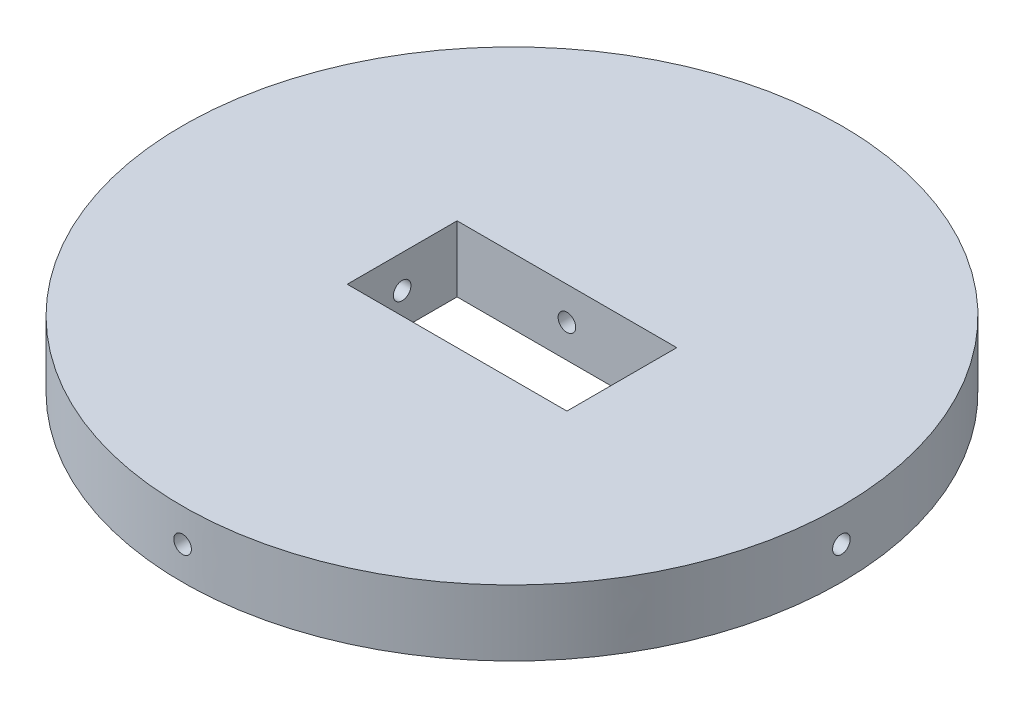
SolidWorks part; units mm, degrees
ref_plane "前视基准面" through (0, 0, 0) normal (0, 0, 1) x (1, 0, 0)
ref_plane "上视基准面" through (0, 0, 0) normal (0, 1, 0) x (1, 0, 0)
ref_plane "右视基准面" through (0, 0, 0) normal (1, 0, 0) x (0, 0, -1)
sketch "草图1" plane through (0, 0, 0) normal (0, 1, 0) x (1, 0, 0)
  circle A0 centre (0, 0) radius 50
  ellipse E0 centre (0, 0) end of major axis (300, 0) minor radius 300
extrude "凸台-拉伸1" add sketch "草图1" along normal blind 60
sketch "草图2" plane through (0, 0, 0) normal (0, 0, 1) x (1, 0, 0)
  line L0 (0, 0) -> (0, 60)
  line L1 (50, 60) -> (-50, 60) construction
  circle A0 centre (0, 30) radius 8
extrude "切除-拉伸1" cut sketch "草图2" against normal through all and the other way through all contours L0 A0 | L0 A0
sketch "草图3" plane through (0, 0, 0) normal (1, 0, 0) x (0, 0, -1)
  line L0 (0, 0) -> (0, 60)
  line L1 (300, 60) -> (-300, 60) construction
  circle A0 centre (0, 30) radius 8
extrude "切除-拉伸2" cut sketch "草图3" against normal through all and the other way through all contours L0 A0 | L0 A0
sketch "草图4" plane through (0, 60, 0) normal (0, 1, 0) x (1, 0, 0)
  line L1 (-100, 50) -> (100, 50)
  line L2 (-100, 50) -> (-100, -50)
  line L3 (-100, -50) -> (100, -50)
  line L4 (100, 50) -> (100, -50)
  line L5 (-100, 50) -> (100, -50) construction
  line L6 (-100, -50) -> (100, 50) construction
  point P0 (0, 0)
  dimension "D1" = 100
  dimension "D2" = 200
extrude "切除-拉伸3" cut sketch "草图4" against normal through all
